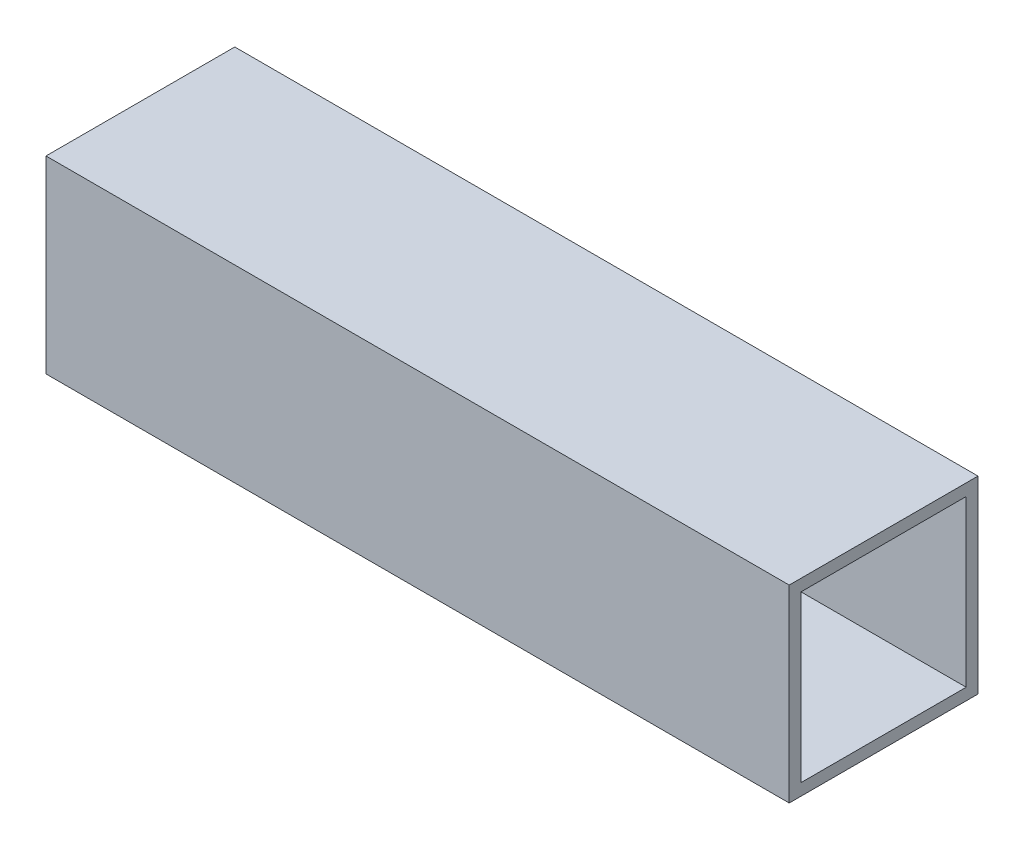
SolidWorks part; units mm, degrees
ref_plane "Front Plane" through (0, 0, 0) normal (0, 0, 1) x (1, 0, 0)
ref_plane "Top Plane" through (0, 0, 0) normal (0, 1, 0) x (1, 0, 0)
ref_plane "Right Plane" through (0, 0, 0) normal (1, 0, 0) x (0, 0, -1)
sketch "Sketch1" plane through (0, 0, 0) normal (1, 0, 0) x (0, 0, -1)
  line L0 (1.5875, 1.5875) -> (23.8125, 1.5875)
  line L1 (0, 0) -> (25.4, 0)
  line L2 (0, 0) -> (0, 25.4)
  line L3 (0, 25.4) -> (25.4, 25.4)
  line L4 (25.4, 0) -> (25.4, 25.4)
  line L5 (23.8125, 1.5875) -> (23.8125, 23.8125)
  line L6 (1.5875, 23.8125) -> (23.8125, 23.8125)
  line L7 (1.5875, 1.5875) -> (1.5875, 23.8125)
  dimension "D1" = 1.5875
  dimension "D2" = 25.4
  dimension "D3" = 25.4
extrude "Boss-Extrude1" add sketch "Sketch1" along normal blind 100
other "PropertyManager"
